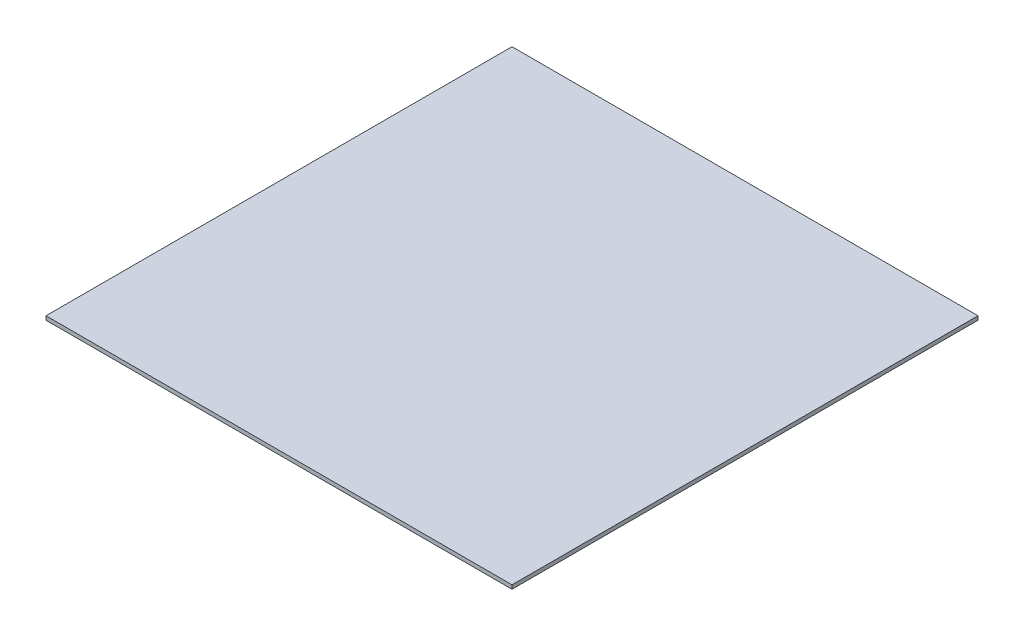
SolidWorks part; units mm, degrees
material "6061-T6 (SS)"
ref_plane "Front Plane" through (0, 0, 0) normal (0, 0, 1) x (1, 0, 0)
ref_plane "Top Plane" through (0, 0, 0) normal (0, 1, 0) x (1, 0, 0)
ref_plane "Right Plane" through (0, 0, 0) normal (1, 0, 0) x (0, 0, -1)
sketch "Sketch2" plane through (0, 0, 0) normal (0, 1, 0) x (1, 0, 0)
  line L1 (381, -381) -> (-381, -381)
  line L2 (381, -381) -> (381, 381)
  line L3 (381, 381) -> (-381, 381)
  line L4 (-381, -381) -> (-381, 381)
  line L5 (381, -381) -> (-381, 381) construction
  line L6 (381, 381) -> (-381, -381) construction
  point P0 (0, 0)
extrude "Boss-Extrude1" add sketch "Sketch2" along normal blind 6.35
